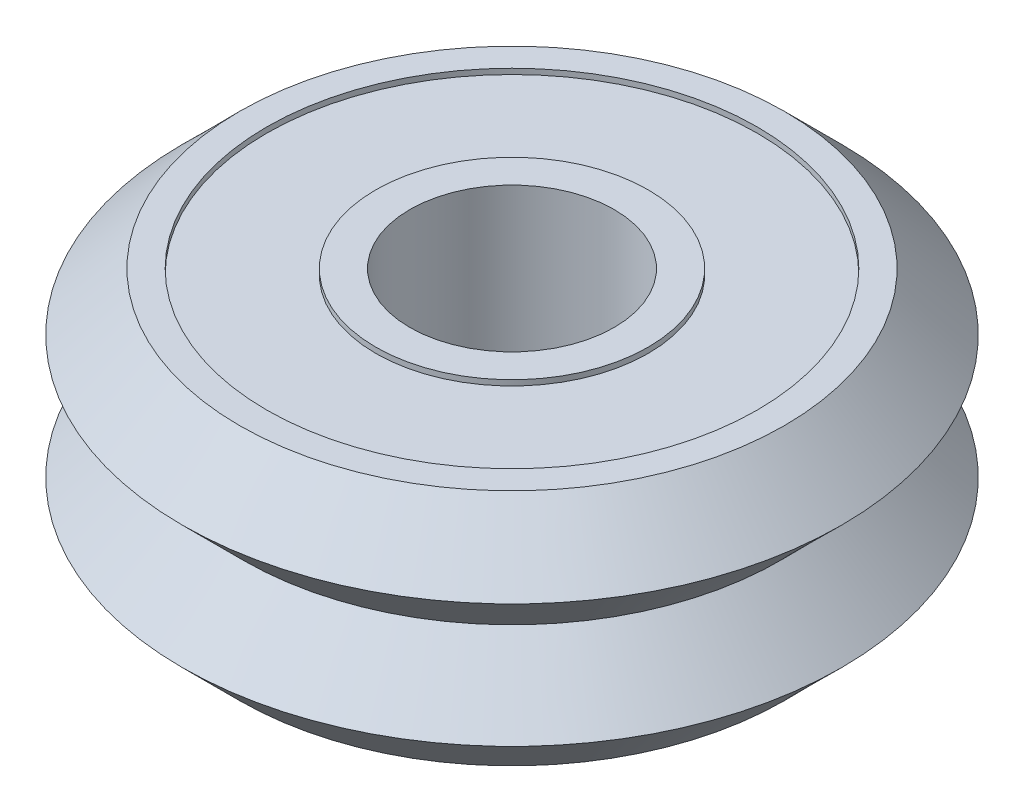
SolidWorks part; units mm, degrees
ref_plane "Front" through (0, 0, 0) normal (0, 0, 1) x (1, 0, 0)
ref_plane "Top" through (0, 0, 0) normal (0, 1, 0) x (1, 0, 0)
ref_plane "Right" through (0, 0, 0) normal (1, 0, 0) x (0, 0, -1)
sketch "Sketch1" plane through (0, 0, 0) normal (0, 0, 1) x (1, 0, 0)
  line L0 (0, 0) -> (0, -50000) construction
  line B0 (-12.69, 5.55) -> (-15.365, 2.875)
  line B1 (-15.365, 2.875) -> (-12.49, 0)
  line B2 (-12.49, 0) -> (-15.365, -2.875)
  line B3 (-15.365, -2.875) -> (-12.69, -5.55)
  line B4 (-12.69, -5.55) -> (-11.43, -5.55)
  line B5 (-11.43, -5.55) -> (-11.43, -5.296)
  line B6 (-11.43, -5.296) -> (-6.35, -5.296)
  line B7 (-6.35, -5.296) -> (-6.35, -5.55)
  line B8 (-6.35, -5.55) -> (-4.7625, -5.55)
  line B9 (-4.7625, -5.55) -> (-4.7625, 5.55)
  line B10 (-4.7625, 5.55) -> (-6.35, 5.55)
  line B11 (-6.35, 5.55) -> (-6.35, 5.296)
  line B12 (-6.35, 5.296) -> (-11.43, 5.296)
  line B13 (-11.43, 5.296) -> (-11.43, 5.55)
  line B14 (-11.43, 5.55) -> (-12.69, 5.55)
  line B15 (-12.49, 0) -> (0, 0) construction
sketch_block_instance "Block1-1"
sketch_block "Block1"
revolve "Revolve1" add sketch "Sketch1" angle 360 about L0
